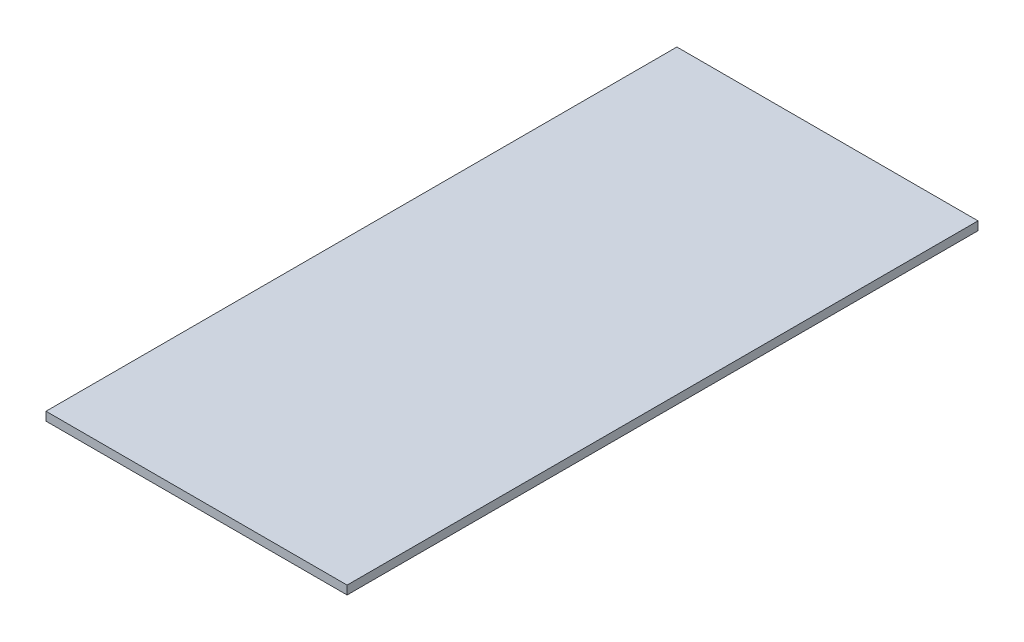
SolidWorks part; units mm, degrees
material "ABS PC"
ref_plane "Front Plane" through (0, 0, 0) normal (0, 0, 1) x (1, 0, 0)
ref_plane "Top Plane" through (0, 0, 0) normal (0, 1, 0) x (1, 0, 0)
ref_plane "Right Plane" through (0, 0, 0) normal (1, 0, 0) x (0, 0, -1)
sketch "Sketch1" plane through (0, 0, 0) normal (0, 1, 0) x (1, 0, 0)
  line L1 (-52.5, 110) -> (52.5, 110)
  line L2 (-52.5, 110) -> (-52.5, -110)
  line L3 (-52.5, -110) -> (52.5, -110)
  line L4 (52.5, 110) -> (52.5, -110)
  line L5 (-52.5, 110) -> (52.5, -110) construction
  line L6 (-52.5, -110) -> (52.5, 110) construction
  point P0 (0, 0)
  dimension "D1" = 220
  dimension "D2" = 105
extrude "Boss-Extrude1" add sketch "Sketch1" along normal blind 3
